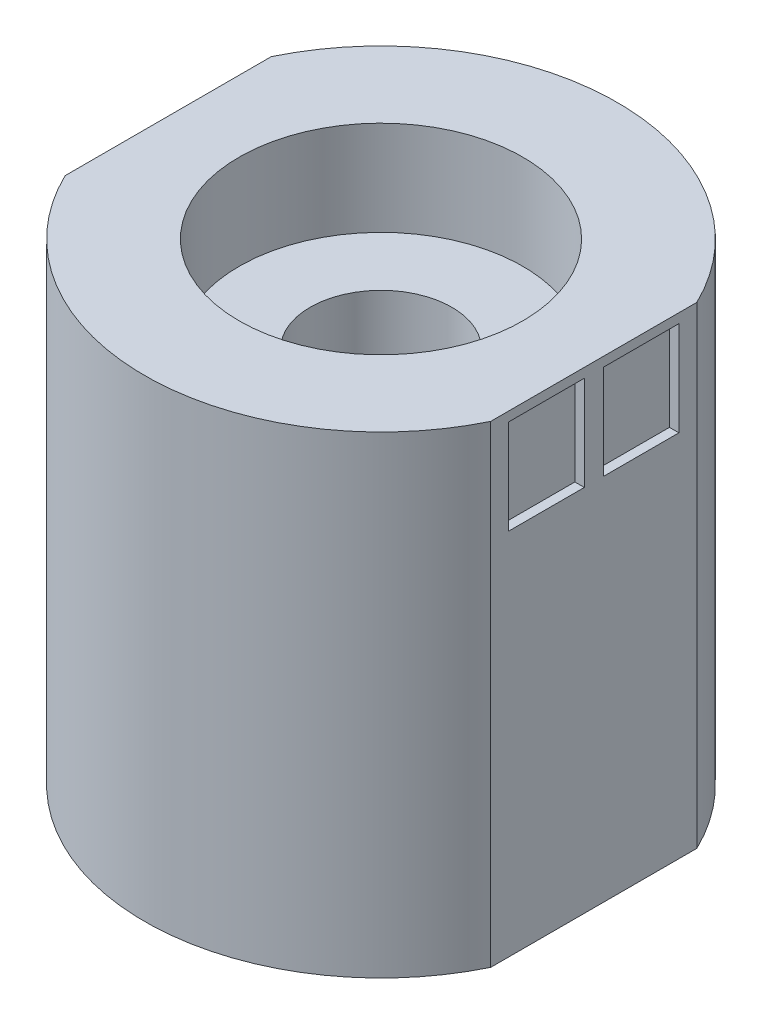
SolidWorks part; units mm, degrees
ref_plane "正面" through (0, 0, 0) normal (0, 0, 1) x (1, 0, 0)
ref_plane "平面" through (0, 0, 0) normal (0, 1, 0) x (1, 0, 0)
ref_plane "右側面" through (0, 0, 0) normal (1, 0, 0) x (0, 0, -1)
sketch "ｽｹｯﾁ1" plane through (0, 0, 0) normal (0, 1, 0) x (1, 0, 0)
  circle A0 centre (0, 0) radius 25
  circle A1 centre (0, 0) radius 7.5
  dimension "D1" = 50
  dimension "D2" = 15
extrude "ﾎﾞｽ - 押し出し1" add sketch "ｽｹｯﾁ1" along normal blind 50
sketch "ｽｹｯﾁ2" plane through (0, 50, 0) normal (0, 1, 0) x (1, 0, 0)
  circle A0 centre (0, 0) radius 15
  circle A1 centre (0, 0) radius 25 construction
  dimension "D1" = 10
extrude "ｶｯﾄ - 押し出し1" cut sketch "ｽｹｯﾁ2" against normal blind 10
sketch "ｽｹｯﾁ3" plane through (0, 50, 0) normal (0, 1, 0) x (1, 0, 0)
  line L0 (-22.5, 10.8972) -> (-22.5, -10.8972)
  line L1 (22.5, 10.8972) -> (22.5, -10.8972)
  circle A0 centre (0, 0) radius 25 construction
  arc A1 (-22.5, 10.8972) -> (22.5, 10.8972) centre (0, 0) cw
  arc A2 (22.5, -10.8972) -> (-22.5, -10.8972) centre (0, 0) cw
  dimension "D1" = 22.5
extrude "ｶｯﾄ - 押し出し2" cut sketch "ｽｹｯﾁ3" against normal through all flip side to cut
sketch "ｽｹｯﾁ4" plane through (-22.5, 0, 0) normal (-1, 0, 0) x (0, 0, 1)
  line L0 (0, 50) -> (0, 0) construction
  line L1 (-9, 49) -> (-1, 49)
  line L2 (-9, 49) -> (-9, 39)
  line L3 (-9, 39) -> (-1, 39)
  line L4 (-1, 49) -> (-1, 39)
  line L9 (-10.8972, 50) -> (10.8972, 50) construction
  line L10 (9, 39) -> (1, 39)
  line L11 (1, 49) -> (1, 39)
  line L12 (9, 49) -> (1, 49)
  line L13 (9, 49) -> (9, 39)
  dimension "D1" = 8
  dimension "D2" = 10
  dimension "D3" = 1
  dimension "D4" = 1
extrude "ｶｯﾄ - 押し出し3" cut sketch "ｽｹｯﾁ4" against normal blind 1
mirror "ﾐﾗｰ1" about plane through (0, 0, 0) normal (1, 0, 0) of "ｶｯﾄ - 押し出し3"
